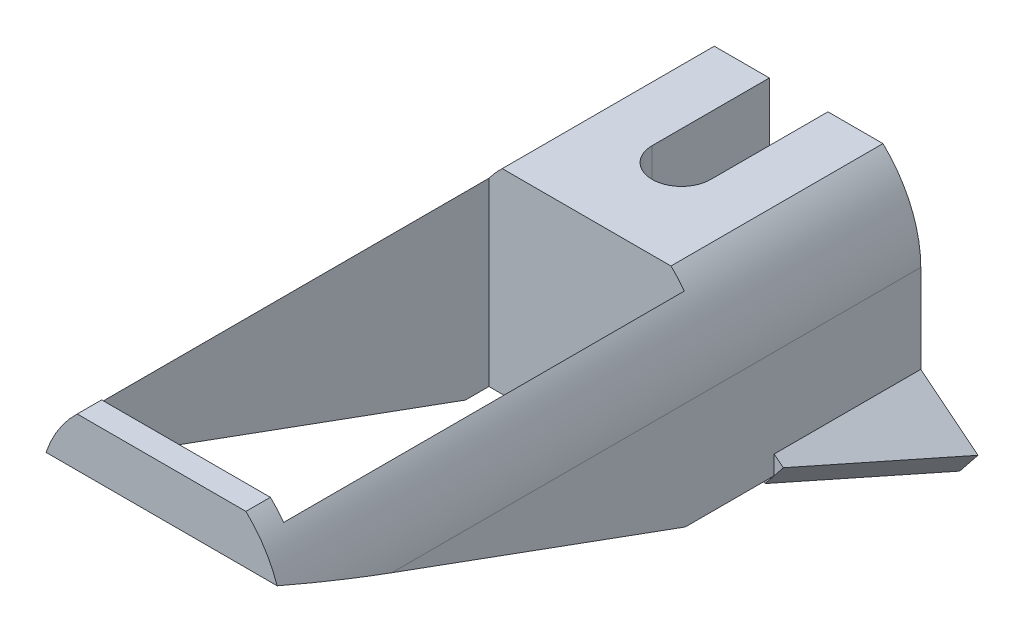
SolidWorks part; units mm, degrees
ref_plane "Alzado" through (0, 0, 0) normal (0, 0, 1) x (1, 0, 0)
ref_plane "Planta" through (0, 0, 0) normal (0, 1, 0) x (1, 0, 0)
ref_plane "Vista lateral" through (0, 0, 0) normal (1, 0, 0) x (0, 0, -1)
sketch "Croquis1" plane through (0, 0, 0) normal (0, 0, 1) x (1, 0, 0)
  line L1 (0, 0) -> (25, 0)
  line L2 (0, 0) -> (0, 20)
  line L3 (0, 20) -> (25, 20)
  line L4 (25, 0) -> (25, 20)
  dimension "D1" = 25
  dimension "D2" = 20
extrude "Saliente-Extruir1" add sketch "Croquis1" along normal blind 21.7
sketch "Croquis2" plane through (0, 0, 21.7) normal (0, 0, 1) x (1, 0, 0)
  line L0 (0, 0) -> (25, 0) construction
  line L1 (0, 20) -> (2.5, 20)
  line L2 (0, 20) -> (0, 0)
  line L3 (0, 0) -> (2.5, 0)
  line L4 (2.5, 20) -> (2.5, 0)
  line L6 (25, 20) -> (22.5, 20)
  line L7 (25, 20) -> (25, 0)
  line L8 (25, 0) -> (22.5, 0)
  line L9 (22.5, 20) -> (22.5, 0)
  dimension "D1" = 2.5
  dimension "D2" = 2.5
extrude "Saliente-Extruir2" add sketch "Croquis2" along normal blind 43.5
sketch "Croquis3" plane through (0, 0, 65.2) normal (0, 0, 1) x (1, 0, 0)
  line L1 (0, 20) -> (25, 20)
  line L2 (0, 20) -> (0, 0)
  line L3 (0, 0) -> (25, 0)
  line L4 (25, 20) -> (25, 0)
extrude "Saliente-Extruir3" add sketch "Croquis3" against normal blind 2.5
sketch "Croquis4" plane through (0, 0, 0) normal (0, -1, 0) x (1, 0, 0)
  line L0 (7, 18.2) -> (18, 18.2) construction
  line L1 (2.5, 62.7) -> (2.5, 21.7) construction
  line L2 (22.5, 62.7) -> (22.5, 21.7) construction
  line L3 (2.5, 21.7) -> (22.5, 21.7) construction
  circle A0 centre (7, 18.2) radius 2.25
  circle A1 centre (18, 18.2) radius 2.25
  dimension "D1" = 4.5
  dimension "D2" = 4.5
  dimension "D3" = 4.5
  dimension "D4" = 3.5
extrude "Cortar-Extruir1" cut sketch "Croquis4" against normal blind 10
sketch "Croquis5" plane through (0, 0, 0) normal (0, -1, 0) x (-1, 0, 0)
  line L0 (-12.5, 0) -> (-12.5, -55.6169) construction
  line L1 (0, 0) -> (-25, 0) construction
  line L2 (-22.5, -42.2) -> (-2.5, -42.2) construction
  line L3 (-22.5, -62.7) -> (-22.5, -21.7) construction
  line L4 (-2.5, -62.7) -> (-2.5, -21.7) construction
  line L5 (-2.5, -21.7) -> (-22.5, -21.7) construction
  point P10 (-12.5, -31.7)
  dimension "D1" = 10
sketch "Croquis6" plane through (0, 0, 0) normal (0, 0, -1) x (-1, 0, 0)
  line L0 (-12.5, 20) -> (-12.5, 0) construction
  line L1 (-25, 20) -> (0, 20) construction
  line L2 (-2.5, 5) -> (-22.5, 5) construction
  line L3 (0, 0) -> (-25, 0) construction
  circle A0 centre (-2.5, 5) radius 2
  circle A1 centre (-22.5, 5) radius 2
  dimension "D1" = 4
  dimension "D2" = 10
  dimension "D3" = 10
  dimension "D4" = 5
extrude "Cortar-Extruir2" cut sketch "Croquis6" against normal blind 10
sketch "Croquis10" plane through (25, 0, 0) normal (1, 0, 0) x (0, 0, -1)
  line L0 (-65.2, 0) -> (-24.1, 0)
  line L2 (-65.2, 0) -> (0, 0) construction
  line L3 (-24.1, 0) -> (-65.2, 15)
  line L4 (-65.2, 0) -> (-65.2, 20) construction
  line L5 (-65.2, 15) -> (-65.2, 0)
  dimension "D1" = 15
  dimension "D2" = 41.1
extrude "Cortar-Extruir4" cut sketch "Croquis10" against normal blind 70
sketch "Croquis11" plane through (0, 0, 0) normal (0, 0, -1) x (-1, 0, 0)
  line L0 (-12.5, 20) -> (-12.5, 0) construction
  line L1 (-25, 20) -> (0, 20) construction
  line L2 (0, 0) -> (-25, 0) construction
  line L3 (-12.5, 10) -> (-25, 0) construction
  line L4 (-25, 1.9209) -> (-30.8565, -2.7643)
  line L6 (-12.5, 10) -> (-33.6293, -6.9034) construction
  line L7 (-25, 0) -> (-25, 20) construction
  line L8 (-30.8565, -2.7643) -> (-28.9824, -5.1069)
  line L9 (-23.1259, -0.4217) -> (-28.9824, -5.1069)
  line L10 (-23.1259, -0.4217) -> (-21.6322, 0.7733)
  line L11 (-21.6322, 0.7733) -> (-25, 1.9209)
  point P16 (-29.9195, -3.9356)
  dimension "D1" = 1.5
  dimension "D2" = 7.5
extrude "Saliente-Extruir5" add sketch "Croquis11" against normal blind 15
sketch "Croquis12" plane through (8.8191, 11.0238, 0) normal (-0.6247, -0.7809, 0) x (0.7809, -0.6247, 0)
  line L0 (19.5217, 15) -> (25.8217, 0)
  line L1 (25.8217, 0) -> (25.8217, 15)
  line L2 (25.8217, 15) -> (19.5217, 15)
extrude "Cortar-Extruir5" cut sketch "Croquis12" against normal blind 15
ref_plane "Plano1" through (12.5, 0, 0) normal (1, 0, 0) x (0, 0, -1)
mirror "Simetría1" about plane through (12.5, 0, 0) normal (1, 0, 0) of "Cortar-Extruir5", "Saliente-Extruir5"
sketch "Croquis13" plane through (0, 0, 0) normal (0, -1, 0) x (1, 0, 0)
  line L0 (12.5, -11.9912) -> (12.5, 11.9912) construction
  line L3 (12.5, 0) -> (12.5, 55.6169) construction
  line L4 (9.5, -11.9912) -> (9.5, 11.9912)
  line L5 (15.5, -11.9912) -> (15.5, 11.9912)
  arc A0 (9.5, -11.9912) -> (15.5, -11.9912) centre (12.5, -11.9912) ccw
  arc A1 (15.5, 11.9912) -> (9.5, 11.9912) centre (12.5, 11.9912) ccw
  point P4 (12.5, 0)
  dimension "D1" = 3
extrude "Cortar-Extruir6" cut sketch "Croquis13" against normal up to surface (20 mm away) up to face at (15, 20, 47.325)
sketch "Croquis14" plane through (0, 0, 0) normal (0, 0, -1) x (-1, 0, 0)
  line L0 (-25, 10.9605) -> (0, 10.9605) construction
  line L1 (-25, 1.9209) -> (-25, 20) construction
  line L2 (0, 20) -> (0, 1.9209) construction
  line L3 (-25, 10.9605) -> (-27.5905, 24.121)
  line L4 (-27.5905, 24.121) -> (2.9936, 24.121)
  line L5 (2.9936, 24.121) -> (0, 10.9605)
  arc A0 (0, 10.9605) -> (-25, 10.9605) centre (-12.5, 10.9605) ccw
extrude "Cortar-Extruir7" cut sketch "Croquis14" against normal up to next
